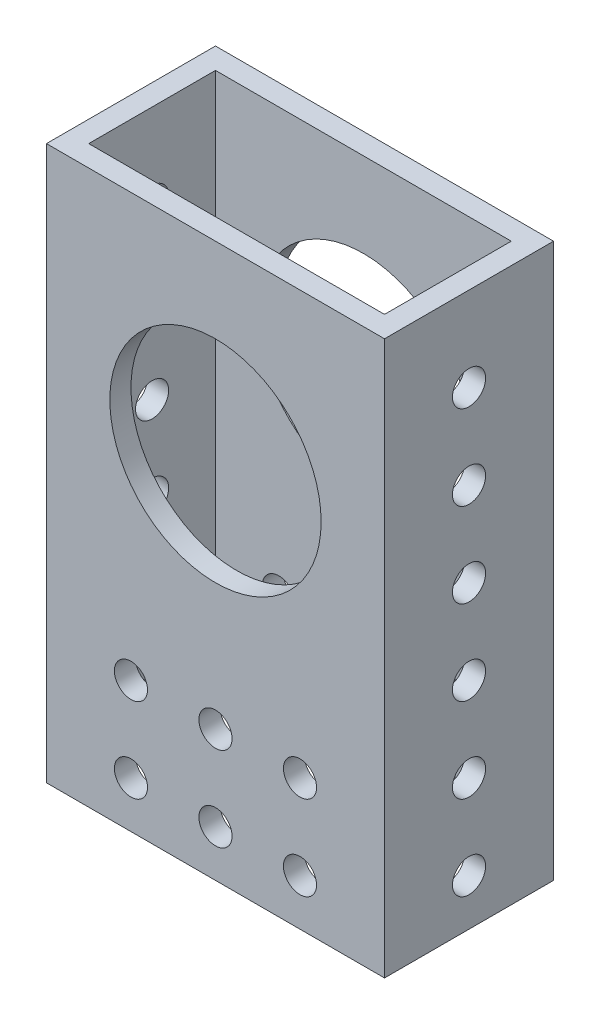
SolidWorks part; units mm, degrees
material "6061-T6 (SS)"
ref_plane "Front Plane" through (0, 0, 0) normal (0, 0, 1) x (1, 0, 0)
ref_plane "Top Plane" through (0, 0, 0) normal (0, 1, 0) x (1, 0, 0)
ref_plane "Right Plane" through (0, 0, 0) normal (1, 0, 0) x (0, 0, -1)
sketch "Sketch1" plane through (0, 0, 0) normal (0, 0, 1) x (1, 0, 0)
  line L0 (25.4, 225.425) -> (25.4, 0) construction
  line L1 (0, 0) -> (50.8, 0)
  line L2 (0, 0) -> (0, 225.425)
  line L3 (0, 225.425) -> (50.8, 225.425)
  line L4 (50.8, 0) -> (50.8, 225.425)
  line L5 (50.8, 9.525) -> (0, 9.525) construction
  circle A0 centre (25.4, 196.85) radius 15.875
  circle A1 centre (25.4, 9.525) radius 2.4892
  circle A2 centre (38.1, 9.525) radius 2.4892
  circle A3 centre (12.7, 9.525) radius 2.4892
  circle A4 centre (12.7, 22.225) radius 2.4892
  circle A5 centre (25.4, 22.225) radius 2.4892
  circle A6 centre (38.1, 22.225) radius 2.4892
  circle A7 centre (12.7, 34.925) radius 2.4892
  circle A8 centre (25.4, 34.925) radius 2.4892
  circle A9 centre (38.1, 34.925) radius 2.4892
  circle A19 centre (12.7, 85.725) radius 2.4892
  circle A20 centre (25.4, 85.725) radius 2.4892
  circle A21 centre (38.1, 85.725) radius 2.4892
  circle A22 centre (12.7, 98.425) radius 2.4892
  circle A23 centre (25.4, 98.425) radius 2.4892
  circle A24 centre (38.1, 98.425) radius 2.4892
  circle A34 centre (12.7, 149.225) radius 2.4892
  circle A35 centre (25.4, 149.225) radius 2.4892
  circle A36 centre (38.1, 149.225) radius 2.4892
  circle A37 centre (12.7, 161.925) radius 2.4892
  circle A38 centre (25.4, 161.925) radius 2.4892
  circle A39 centre (38.1, 161.925) radius 2.4892
  circle A40 centre (38.1, 47.625) radius 2.4892 [skipped]
  circle A41 centre (25.4, 47.625) radius 2.4892 [skipped]
  circle A42 centre (12.7, 47.625) radius 2.4892 [skipped]
  circle A43 centre (12.7, 60.325) radius 2.4892 [skipped]
  circle A44 centre (25.4, 60.325) radius 2.4892 [skipped]
  circle A45 centre (38.1, 60.325) radius 2.4892 [skipped]
  circle A46 centre (38.1, 73.025) radius 2.4892 [skipped]
  circle A47 centre (25.4, 73.025) radius 2.4892 [skipped]
  circle A48 centre (12.7, 73.025) radius 2.4892 [skipped]
  circle A49 centre (12.7, 123.825) radius 2.4892 [skipped]
  circle A50 centre (12.7, 136.525) radius 2.4892 [skipped]
  circle A51 centre (38.1, 136.525) radius 2.4892 [skipped]
  circle A52 centre (38.1, 123.825) radius 2.4892 [skipped]
  circle A53 centre (12.7, 111.125) radius 2.4892 [skipped]
  circle A54 centre (38.1, 111.125) radius 2.4892 [skipped]
  circle A55 centre (25.4, 136.525) radius 2.4892 [skipped]
  circle A56 centre (25.4, 123.825) radius 2.4892 [skipped]
  circle A57 centre (25.4, 111.125) radius 2.4892 [skipped]
  dimension "D3" = 31.75
  dimension "D5" = 4.9784
  dimension "D1" = 50.8
  dimension "D2" = 225.425
  dimension "D4" = 196.85
  dimension "D6" = 9.525
  dimension "D7" = 12.7
  dimension "D8" = 12.7
  dimension "D10" = 12.7
  dimension "D9" = 13
extrude "Boss-Extrude1" add sketch "Sketch1" along normal blind 25.4
sketch "Sketch2" plane through (50.8, 0, 0) normal (1, 0, 0) x (0, 0, -1)
  line L0 (-12.7, 0) -> (-12.7, 225.425) construction
  line L1 (-25.4, 0) -> (0, 0) construction
  line L2 (-25.4, 225.425) -> (0, 225.425) construction
  circle A0 centre (-12.7, 9.525) radius 2.4892
  circle A1 centre (-12.7, 22.225) radius 2.4892
  circle A2 centre (-12.7, 34.925) radius 2.4892
  circle A3 centre (-12.7, 47.625) radius 2.4892
  circle A4 centre (-12.7, 60.325) radius 2.4892
  circle A5 centre (-12.7, 73.025) radius 2.4892
  circle A6 centre (-12.7, 85.725) radius 2.4892
  circle A7 centre (-12.7, 98.425) radius 2.4892
  circle A8 centre (-12.7, 111.125) radius 2.4892
  circle A9 centre (-12.7, 123.825) radius 2.4892
  circle A10 centre (-12.7, 136.525) radius 2.4892
  circle A11 centre (-12.7, 149.225) radius 2.4892
  circle A12 centre (-12.7, 161.925) radius 2.4892
  circle A13 centre (-12.7, 174.625) radius 2.4892
  circle A14 centre (-12.7, 187.325) radius 2.4892
  circle A15 centre (-12.7, 200.025) radius 2.4892
  circle A16 centre (-12.7, 212.725) radius 2.4892
  dimension "D2" = 4.9784
  dimension "D1" = 9.525
  dimension "D4" = 12.7
  dimension "D3" = 17
extrude "Cut-Extrude1" cut sketch "Sketch2" against normal through all
sketch "Sketch3" plane through (0, 225.425, 0) normal (0, 1, 0) x (1, 0, 0)
  line L8 (47.625, -3.175) -> (3.175, -3.175)
  line L9 (3.175, -3.175) -> (3.175, -22.225)
  line L10 (3.175, -22.225) -> (47.625, -22.225)
  line L11 (47.625, -22.225) -> (47.625, -3.175)
  line L12 (47.625, -3.175) -> (3.175, -3.175)
  line L13 (3.175, -3.175) -> (3.175, -22.225)
  line L14 (3.175, -22.225) -> (47.625, -22.225)
  line L15 (47.625, -22.225) -> (47.625, -3.175)
  dimension "D1" = 3.175
extrude "Cut-Extrude2" cut sketch "Sketch3" against normal through all
sketch "Sketch4" plane through (0, 0, 25.4) normal (0, 0, 1) x (1, 0, 0)
  line L0 (0, 225.425) -> (0, 0) construction
  line L1 (0, 142.24) -> (50.8, 142.24)
  line L2 (0, 142.24) -> (0, 0)
  line L3 (0, 0) -> (50.8, 0)
  line L4 (50.8, 142.24) -> (50.8, 0)
  dimension "D1" = 142.24
extrude "Cut-Extrude3" cut sketch "Sketch4" against normal through all
